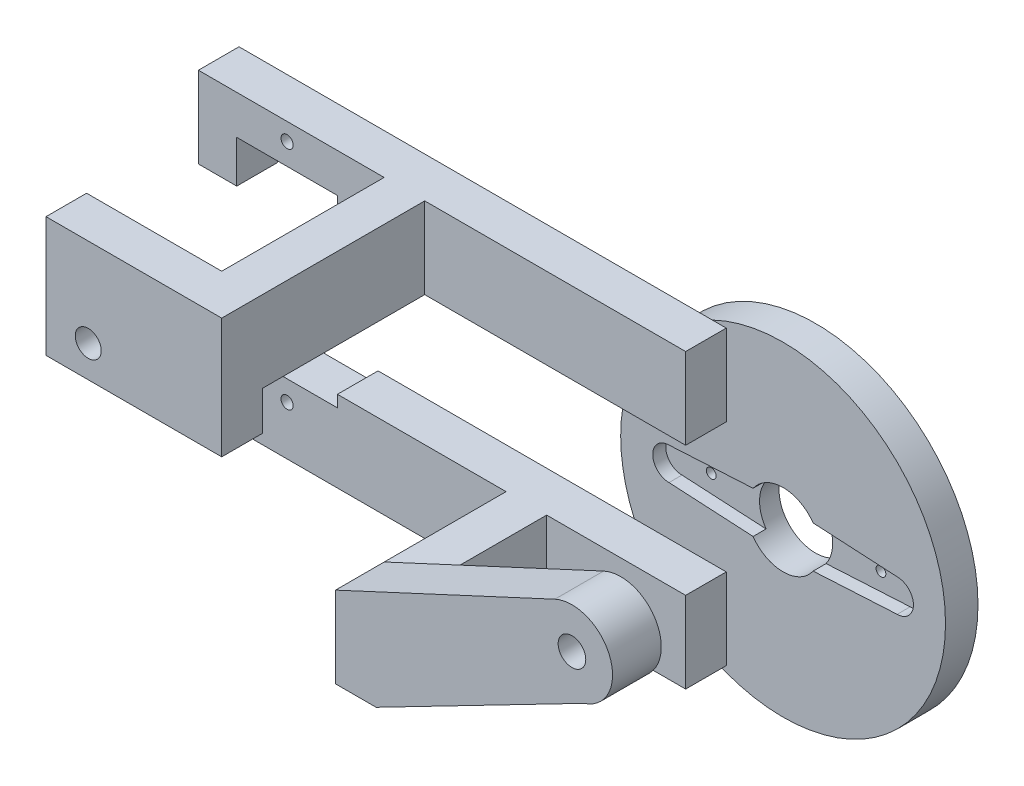
SolidWorks part; units mm, degrees
ref_plane "Front Plane" through (0, 0, 0) normal (0, 0, 1) x (1, 0, 0)
ref_plane "Top Plane" through (0, 0, 0) normal (0, 1, 0) x (1, 0, 0)
ref_plane "Right Plane" through (0, 0, 0) normal (1, 0, 0) x (0, 0, -1)
sketch "Sketch1" plane through (0, 0, 0) normal (0, 0, 1) x (1, 0, 0)
  line L0 (-14.05, 2) -> (-2.2091, 2.65)
  line L1 (2.2091, 2.65) -> (14.05, 2)
  line L2 (14.05, -2) -> (2.2091, -2.65)
  line L3 (-14.05, -2) -> (-2.2091, -2.65)
  arc A1 (2.2091, 2.65) -> (-2.2091, 2.65) centre (0, 0) ccw
  arc A2 (14.05, -2) -> (14.05, 2) centre (14.05, 0) ccw
  arc A3 (-14.05, 2) -> (-14.05, -2) centre (-14.05, 0) ccw
  arc A4 (-2.2091, -2.65) -> (2.2091, -2.65) centre (0, 0) ccw
  circle A5 centre (0, 0) radius 20
  dimension "D1" = 40
  dimension "D2" = 2
  dimension "D3" = 3.45
extrude "Boss-Extrude1" add sketch "Sketch1" against normal blind 4
sketch "Sketch2" plane through (0, 0, -4) normal (0, 0, -1) x (-1, 0, 0)
  line L0 (14.05, 2) -> (2.2091, 2.65)
  line L1 (14.05, -2) -> (2.2091, -2.65)
  line L2 (-2.2091, -2.65) -> (-14.05, -2)
  line L3 (-2.2091, 2.65) -> (-14.05, 2)
  arc A0 (14.05, -2) -> (14.05, 2) centre (14.05, 0) ccw
  arc A1 (-14.05, 2) -> (-14.05, -2) centre (-14.05, 0) ccw
  arc A2 (2.2091, -2.65) -> (2.2091, 2.65) centre (0, 0) ccw
  arc A3 (-2.2091, 2.65) -> (-2.2091, -2.65) centre (0, 0) ccw
extrude "Boss-Extrude2" add sketch "Sketch2" against normal blind 2.4
sketch "Sketch6" plane through (0, 0, 0) normal (0, 0, 1) x (1, 0, 0)
  line L0 (-20, 0) -> (20, 0) construction
  line L1 (0, 20) -> (0, -20) construction
  line L2 (-67, 8) -> (-7, 8)
  line L3 (-67, 8) -> (-67, 18)
  line L4 (-67, 18) -> (-7, 18)
  line L5 (-7, 8) -> (-7, 18)
  line L6 (-37, 18) -> (-37, 8) construction
  line L7 (-67, 13) -> (-7, 13) construction
  line L8 (-67, -18) -> (-7, -18)
  line L9 (-7, -8) -> (-7, -18)
  line L10 (-67, -8) -> (-7, -8)
  line L11 (-67, -8) -> (-67, -18)
  circle A0 centre (0, 0) radius 20 construction
  point P377 (-37, 13)
  dimension "D1" = 10
  dimension "D2" = 60
  dimension "D3" = 7
  dimension "D4" = 8
extrude "Boss-Extrude5" add sketch "Sketch6" along normal blind 5
sketch "Sketch7" plane through (0, 0, 0) normal (0, 0, -1) x (-1, 0, 0)
  circle A0 centre (56.0783, 15.85) radius 0.75
  circle A1 centre (56.0783, -11.95) radius 0.75
  dimension "D1" = 1.5
  dimension "D2" = 1.5
extrude "Cut-Extrude1" cut sketch "Sketch7" against normal blind 5
sketch "Sketch8" plane through (0, 0, 5) normal (0, 0, 1) x (1, 0, 0)
  line L0 (-67, 8) -> (-7, 8) construction
  line L1 (-44.1293, 8) -> (-39.1293, 8)
  line L2 (-44.1293, 8) -> (-44.1293, 18)
  line L3 (-44.1293, 18) -> (-39.1293, 18)
  line L4 (-39.1293, 8) -> (-39.1293, 18)
  line L5 (-41.6293, 18) -> (-41.6293, 8) construction
  line L6 (-44.1293, 13) -> (-39.1293, 13) construction
  line L7 (-7, 18) -> (-67, 18) construction
  point P168 (-41.6293, 13)
  dimension "D1" = 5
extrude "Boss-Extrude6" add sketch "Sketch8" along normal blind 20
sketch "Sketch9" plane through (0, 0, 25) normal (0, 0, 1) x (1, 0, 0)
  line L1 (-39.1293, 18) -> (-60.7669, 18)
  line L2 (-39.1293, 18) -> (-39.1293, 3.2)
  line L3 (-39.1293, 3.2) -> (-60.7669, 3.2)
  line L4 (-60.7669, 18) -> (-60.7669, 3.2)
  line L5 (-49.9481, 3.2) -> (-49.9481, 18) construction
  line L6 (-39.1293, 10.6) -> (-60.7669, 10.6) construction
  circle A0 centre (-55.5659, 7.0907) radius 1.6
  point P247 (-49.9481, 10.6)
  dimension "D1" = 3.2
  dimension "D2" = 14.8
extrude "Boss-Extrude7" add sketch "Sketch9" along normal blind 5
sketch "Sketch10" plane through (0, 0, 5) normal (0, 0, 1) x (1, 0, 0)
  line L0 (-62.2783, -4.9571) -> (-62.2783, -50004.9571) construction
  line L2 (-60.4888, -9.397) -> (49939.5112, -9.397) construction
  line L3 (-61.1188, 13.2) -> (-50061.1188, 13.2) construction
  line L5 (-49.8783, -6.4125) -> (-49.8783, -50006.4125) construction
  line L8 (-62.2783, -9.4495) -> (-49.8783, -9.4495)
  line L9 (-62.2783, -9.4495) -> (-62.2783, 13.2)
  line L10 (-62.2783, 13.2) -> (-49.8783, 13.2)
  line L11 (-49.8783, -9.4495) -> (-49.8783, 13.2)
  line L12 (-56.0783, 13.2) -> (-56.0783, -9.4495) construction
  line L13 (-62.2783, 1.8753) -> (-49.8783, 1.8753) construction
  point P320 (-56.0783, 1.8753)
extrude "Cut-Extrude2" cut sketch "Sketch10" against normal through all
sketch "Sketch11" plane through (0, 0, 0) normal (0, 0, 1) x (1, 0, 0)
  circle A0 centre (-10.45, 0) radius 0.6
  circle A1 centre (10.45, 0) radius 0.6
extrude "Cut-Extrude3" cut sketch "Sketch11" against normal blind 10
sketch "Sketch12" plane through (0, 0, -4) normal (0, 0, -1) x (-1, 0, 0)
  circle A0 centre (0, 0) radius 4.5
  dimension "D1" = 9
extrude "Cut-Extrude4" cut sketch "Sketch12" against normal blind 5
sketch "Sketch14" plane through (0, 0, 5) normal (0, 0, 1) x (1, 0, 0)
  line L0 (-67, -18) -> (-7, -18) construction
  line L1 (-29.1151, -18) -> (-24.1151, -18)
  line L2 (-29.1151, -18) -> (-29.1151, -8)
  line L3 (-29.1151, -8) -> (-24.1151, -8)
  line L4 (-24.1151, -18) -> (-24.1151, -8)
  line L5 (-26.6151, -8) -> (-26.6151, -18) construction
  line L6 (-29.1151, -13) -> (-24.1151, -13) construction
  line L7 (-7, -8) -> (-49.8783, -8) construction
  point P192 (-26.6151, -13)
  dimension "D1" = 5
extrude "Boss-Extrude9" add sketch "Sketch14" along normal blind 21
sketch "Sketch15" plane through (0, 0, 26) normal (0, 0, 1) x (1, 0, 0)
  line L0 (-29.1151, -8) -> (-2.1049, 4.5354)
  line L1 (-24.1151, -18) -> (1.4919, -4.7723)
  line L2 (-29.1151, -8) -> (-29.1151, -18)
  line L3 (-29.1151, -18) -> (-24.1151, -18)
  circle A0 centre (0, 0) radius 1.7
  arc A1 (1.4919, -4.7723) -> (-2.1049, 4.5354) centre (0, 0) ccw
  dimension "D1" = 3.4
  dimension "D2" = 10
extrude "Boss-Extrude10" add sketch "Sketch15" against normal blind 6
